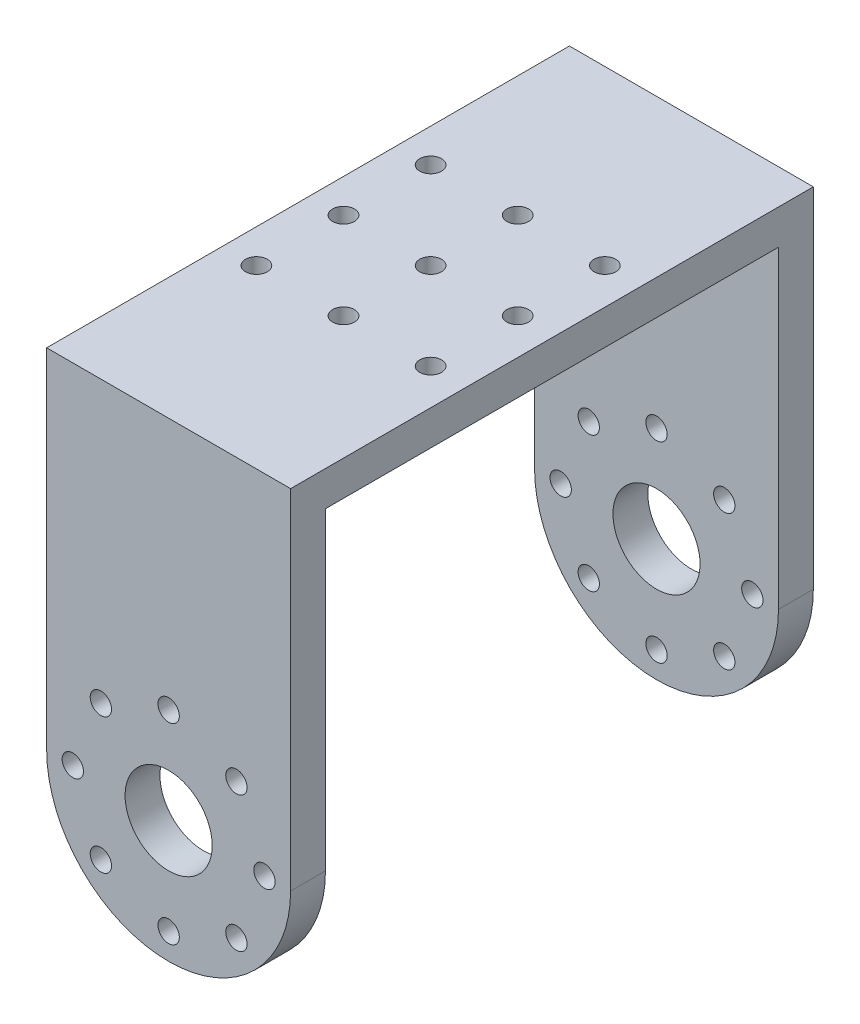
SolidWorks part; units mm, degrees
ref_plane "정면" through (0, 0, 0) normal (0, 0, 1) x (1, 0, 0)
ref_plane "윗면" through (0, 0, 0) normal (0, 1, 0) x (1, 0, 0)
ref_plane "우측면" through (0, 0, 0) normal (1, 0, 0) x (0, 0, -1)
sketch "스케치2" plane through (0, 0, 0) normal (0, 0, 1) x (1, 0, 0)
  line L2 (-14, 0) -> (-14, 40)
  line L3 (-14, 40) -> (14, 40)
  line L4 (14, 0) -> (14, 40)
  arc A0 (-14, 0) -> (14, 0) centre (0, 0) ccw
  circle A18 centre (0, 0) radius 5
  circle A20 centre (0, 11) radius 1.225
  circle A22 centre (7.7782, 7.7782) radius 1.225
  circle A24 centre (11, 0) radius 1.225
  circle A25 centre (7.7782, -7.7782) radius 1.225
  circle A27 centre (0, -11) radius 1.225
  circle A28 centre (-7.7782, -7.7782) radius 1.225
  circle A30 centre (-11, 0) radius 1.225
  circle A31 centre (-7.7782, 7.7782) radius 1.225
  dimension "D1" = 10
  dimension "D3" = 2.45
  dimension "D5" = 14
  dimension "D2" = 40
  dimension "D4" = 11
  dimension "D7" = 7.7782
  dimension "D9" = 11
  dimension "D11" = 7.7782
  dimension "D14" = 7.7782
  dimension "D15" = 11
  dimension "D16" = 7.7782
  dimension "D18" = 11
extrude "보스-돌출1" add sketch "스케치2" along normal blind 60
sketch "스케치9" plane through (14, 0, 0) normal (1, 0, 0) x (0, 0, -1)
  line L0 (-60, -14) -> (0, -14) construction
  line L1 (-56, 36) -> (-4, 36)
  line L2 (-56, 36) -> (-56, -14)
  line L3 (-56, -14) -> (-4, -14)
  line L4 (-4, 36) -> (-4, -14)
  line L5 (-60, 40) -> (0, 40) construction
  line L7 (0, 0) -> (0, 40) construction
  dimension "D1" = 4
  dimension "D3" = 4
  dimension "D4" = 52
extrude "컷-돌출1" cut sketch "스케치9" against normal blind 60
sketch "스케치11" plane through (0, 40, 0) normal (0, 1, 0) x (1, 0, 0)
  line L0 (0, 0) -> (0, -45.5818) construction
  line L1 (14, 0) -> (-14, 0) construction
  line L3 (14, -30) -> (-14, -30) construction
  line L4 (14, -60) -> (14, 0) construction
  line L5 (-14, -60) -> (-14, 0) construction
  circle A0 centre (-10.1427, -39.7863) radius 1.25
  circle A1 centre (-10.1427, -19.7863) radius 1.25
  circle A2 centre (-10.1427, -29.7863) radius 1.25
  circle A3 centre (-0.1427, -39.7863) radius 1.25
  circle A4 centre (-0.1427, -29.7863) radius 1.25
  circle A5 centre (-0.1427, -19.7863) radius 1.25
  circle A6 centre (9.8573, -19.7863) radius 1.25
  circle A7 centre (9.8573, -29.7863) radius 1.25
  circle A8 centre (9.8573, -39.7863) radius 1.25
  dimension "D1" = 2.5
  dimension "D2" = 3.8573
  dimension "D3" = 13.8573
  dimension "D4" = 23.8573
  dimension "D5" = 19.7863
  dimension "D6" = 29.7863
  dimension "D7" = 39.7863
extrude "컷-돌출3" cut sketch "스케치11" against normal blind 60
